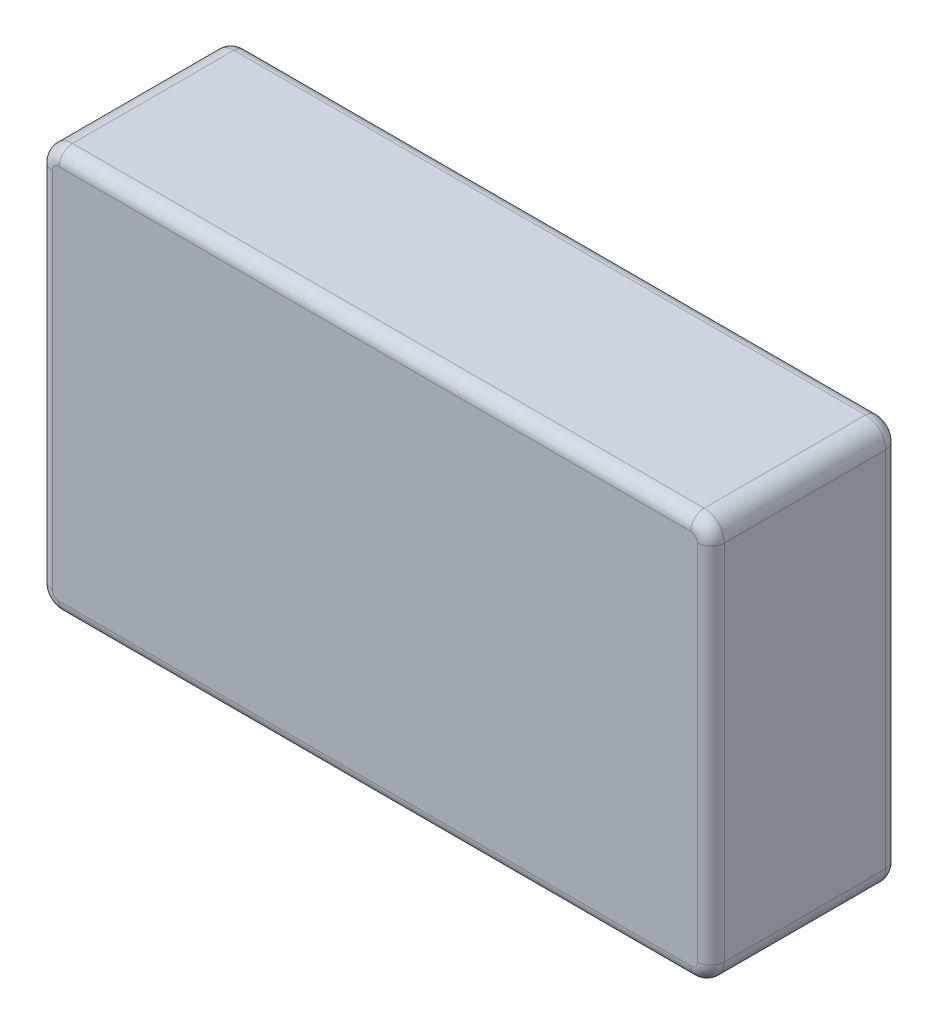
SolidWorks part; units mm, degrees
material "ABS PC"
ref_plane "Front Plane" through (0, 0, 0) normal (0, 0, 1) x (1, 0, 0)
ref_plane "Top Plane" through (0, 0, 0) normal (0, 1, 0) x (1, 0, 0)
ref_plane "Right Plane" through (0, 0, 0) normal (1, 0, 0) x (0, 0, -1)
sketch "Block sketch 1" plane through (0, 0, 0) normal (0, 0, 1) x (1, 0, 0)
  line L0 (535, -110) -> (629, -110)
  line L1 (632, -107) -> (632, -53)
  line L2 (629, -50) -> (535, -50)
  line L3 (532, -53) -> (532, -107)
  arc A0 (629, -110) -> (632, -107) centre (629, -107) ccw
  arc A1 (632, -53) -> (629, -50) centre (629, -53) ccw
  arc A2 (535, -50) -> (532, -53) centre (535, -53) ccw
  arc A3 (532, -107) -> (535, -110) centre (535, -107) ccw
  dimension "D1" = 3
  dimension "D2" = 100
  dimension "D3" = 60
extrude "Block 1" add sketch "Block sketch 1" along normal blind 28 from offset 323 separate body
fillet "Block edge fillet 1" radius 2 16 edges at (532.8787, -109.1213, 351) (532.8787, -50.8787, 351) (631.1213, -50.8787, 351) (631.1213, -109.1213, 351) (631.1213, -50.8787, 323) (631.1213, -109.1213, 323) (582, -110, 323) (532.8787, -109.1213, 323) (532, -80, 323) (532.8787, -50.8787, 323) (632, -80, 351) (532, -80, 351) (582, -50, 351) (582, -110, 351) (632, -80, 323) (582, -50, 323)
